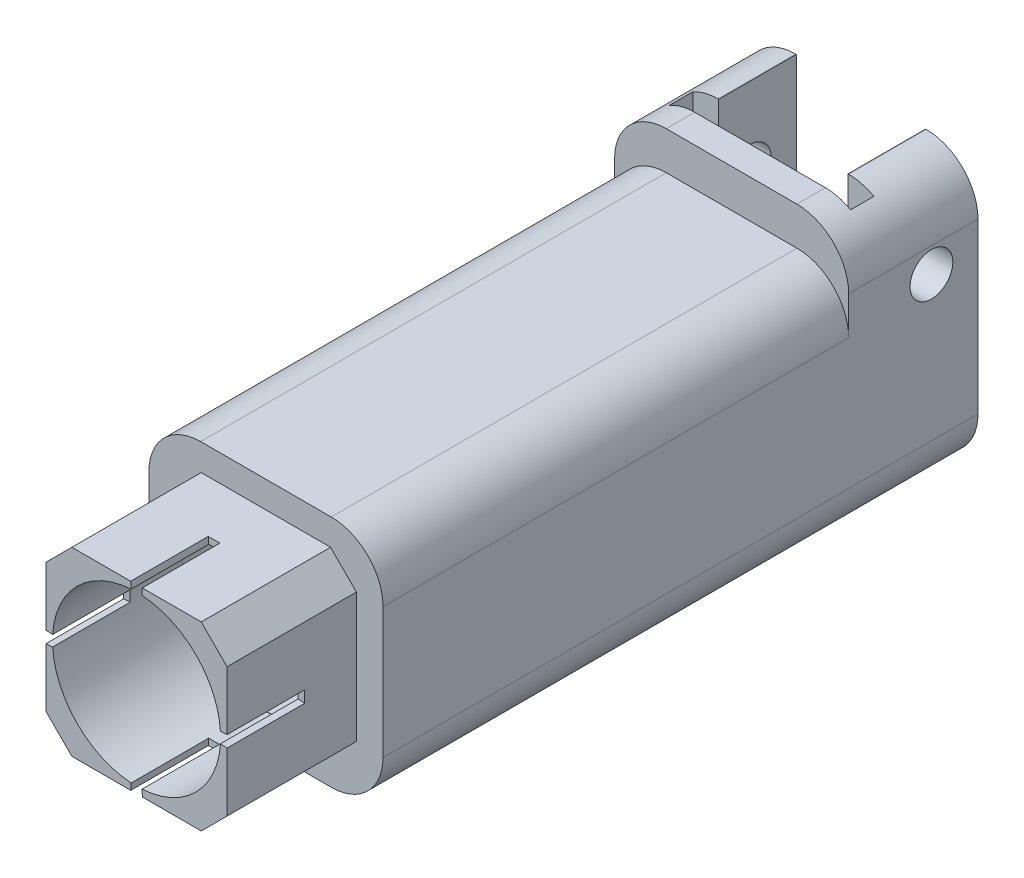
SolidWorks part; units mm, degrees
ref_plane "Front Plane" through (0, 0, 0) normal (0, 0, 1) x (1, 0, 0)
ref_plane "Top Plane" through (0, 0, 0) normal (0, 1, 0) x (1, 0, 0)
ref_plane "Right Plane" through (0, 0, 0) normal (1, 0, 0) x (0, 0, -1)
sketch "Sketch1" plane through (0, 0, 0) normal (0, 0, 1) x (1, 0, 0)
  line L0 (-5.05, 9.05) -> (5.05, 9.05)
  line L1 (9.05, -5.05) -> (9.05, 5.05)
  line L2 (0, 0) -> (0, 14.1446) construction
  line L3 (-9.05, -5.05) -> (-9.05, 5.05)
  line L4 (-12.732, 0) -> (15.0845, 0) construction
  line L5 (-5.05, -9.05) -> (5.05, -9.05)
  arc A4 (5.05, 9.05) -> (9.05, 5.05) centre (5.05, 5.05) cw
  arc A5 (9.05, -5.05) -> (5.05, -9.05) centre (5.05, -5.05) cw
  arc A6 (-5.05, -9.05) -> (-9.05, -5.05) centre (-5.05, -5.05) cw
  arc A7 (-9.05, 5.05) -> (-5.05, 9.05) centre (-5.05, 5.05) cw
  point P11 (9.05, 0)
  point P12 (0, 9.05)
  point P20 (0, -9.05)
  point P21 (-9.05, 0)
  dimension "D3" = 0
  dimension "D1" = 5.05
  dimension "D2" = 5.05
  dimension "D4" = 9.05
  dimension "D5" = 9.05
extrude "Boss-Extrude1" add sketch "Sketch1" along normal blind 46
sketch "Sketch15" plane through (0, 0, 0) normal (0, 0, 1) x (1, 0, 0)
  line L0 (9.05, -5.05) -> (9.05, 5.05) construction
  line L6 (-5.05, -9.05) -> (5.05, -9.05)
  line L7 (-9.05, -5.05) -> (-9.05, 8)
  line L8 (-5.05, 12) -> (5.05, 12)
  line L9 (9.05, -5.05) -> (9.05, 8)
  line L10 (-5.05, -9.05) -> (5.05, -9.05) construction
  line L11 (-9.05, -5.05) -> (-9.05, 5.05) construction
  arc A4 (-5.05, -9.05) -> (-9.05, -5.05) centre (-5.05, -5.05) cw
  arc A5 (5.05, -9.05) -> (9.05, -5.05) centre (5.05, -5.05) ccw
  arc A6 (5.05, 12) -> (9.05, 8) centre (5.05, 8) cw
  arc A7 (-9.05, 8) -> (-5.05, 12) centre (-5.05, 8) cw
  point P0 (0, 0)
  dimension "D2" = 0
  dimension "D5" = 4
  dimension "D1" = 12
  dimension "D3" = 0
  dimension "D4" = 0
extrude "Boss-Extrude3" add sketch "Sketch15" along normal blind 10
sketch "Sketch17" plane through (9.05, 0, 0) normal (1, 0, 0) x (0, 0, -1)
  line L2 (0, -5.05) -> (0, 5.05) construction
  line L3 (-10, 12) -> (0, 12) construction
  circle A0 centre (-3.6, 6.1) radius 1.655
  dimension "D1" = 3.31
  dimension "D2" = 3.6
  dimension "D3" = 5.9
extrude "Cut-Extrude10" cut sketch "Sketch17" against normal blind 30
sketch "Sketch18" plane through (0, 0, 0) normal (0, 0, 1) x (1, 0, 0)
  line L82 (-4.9965, -4.2592) -> (-3.8511, -6.9461)
  line L83 (-3.8511, -6.9461) -> (-2.0485, -4.5591)
  line L86 (-2.0485, -4.5591) -> (-0.5631, -7.2172)
  line L87 (-0.5631, -7.2172) -> (0.9839, -4.6242)
  line L88 (0.9839, -4.6242) -> (2.7048, -7.2172)
  line L91 (2.7048, -7.2172) -> (3.4697, -4.8701)
  line L92 (3.4697, -4.8701) -> (4.6745, -7.0261)
  line L93 (4.6745, -7.0261) -> (4.9982, -5.6687)
  line L94 (-4.9965, -4.2592) -> (-4.9965, 5.3735)
  line L95 (-4.9965, 5.3735) -> (4.9982, 5.3735)
  line L96 (4.9982, 5.3735) -> (4.9982, -5.6687)
  dimension "D1" = 4.9965
  dimension "D2" = 4.9982
extrude "Cut-Extrude11" cut sketch "Sketch18" along normal blind 6
sketch "Sketch20" plane through (0, 0, 6) normal (0, 0, -1) x (-1, 0, 0)
  line L0 (-7, 0) -> (-7, 13.4738)
  line L1 (-7, 13.4738) -> (7, 13.4738)
  line L2 (7, 13.4738) -> (7, 0)
  line L3 (-7, 0) -> (-7, -7.1944)
  line L4 (-7, -7.1944) -> (7, -7.1944)
  line L5 (7, -7.1944) -> (7, 0)
  dimension "D2" = 7
extrude "Cut-Extrude12" cut sketch "Sketch20" against normal blind 1.8
sketch "Sketch21" plane through (0, 0, 0) normal (0, 0, 1) x (1, 0, 0)
  line L0 (-12.732, 0) -> (15.0845, 0) construction
  line L3 (5, 17.4937) -> (-5, 17.4937)
  line L4 (-5, 0) -> (-5, 17.4937)
  line L8 (5, 0) -> (5, -0.5)
  line L9 (5, -0.5) -> (-5, -0.5)
  line L10 (-5, -0.5) -> (-5, 0)
  line L11 (5, 0) -> (5, 17.4937)
  dimension "D1" = 5
  dimension "D2" = 5
  dimension "D3" = 0.5
extrude "Cut-Extrude13" cut sketch "Sketch21" along normal blind 7.2
sketch "Sketch22" plane through (0, 0, 46) normal (0, 0, 1) x (1, 0, 0)
  line L0 (-5.0065, -7.0039) -> (4.9935, -7.0039)
  line L1 (-7.0065, -5.0039) -> (-7.0065, 4.9961)
  line L2 (-5.0065, 6.9961) -> (4.9935, 6.9961)
  line L3 (6.9935, -5.0039) -> (6.9935, 4.9961)
  line L4 (-7.0065, -7.0039) -> (6.9935, 6.9961) construction
  line L5 (-7.0065, 6.9961) -> (6.9935, -7.0039) construction
  line L6 (4.9935, 6.9961) -> (6.9935, 4.9961)
  line L7 (-5.0065, 6.9961) -> (-7.0065, 4.9961)
  line L8 (-7.0065, -5.0039) -> (-5.0065, -7.0039)
  line L9 (4.9935, -7.0039) -> (6.9935, -5.0039)
  circle A0 centre (-0.0065, -0.0039) radius 6.5
  point P2 (-0.0065, -0.0039)
  dimension "D2" = 13
  dimension "D1" = 14
  dimension "D3" = 0
extrude "Boss-Extrude4" add sketch "Sketch22" along normal blind 10
sketch "Sketch23" plane through (0, 0, 56) normal (0, 0, 1) x (1, 0, 0)
  line L0 (0, 0) -> (7, 0.45)
  line L1 (7, 0.45) -> (7, -0.45)
  line L2 (7, -0.45) -> (0, 0)
  dimension "D1" = 0.45
  dimension "D2" = 0.45
  dimension "D3" = 0
  dimension "D4" = 0
extrude "Cut-Extrude14" cut sketch "Sketch23" against normal blind 6
pattern_circular "CirPattern1" count 4 every 90 about axis through (-0.0065, -0.0039, 0) along (0, 0, 1) of "Cut-Extrude14"
sketch "Sketch24" plane through (0, 0, 46) normal (0, 0, 1) x (1, 0, 0)
  circle A0 centre (0, 0) radius 6.4924
extrude "Cut-Extrude15" cut sketch "Sketch24" against normal blind 35
